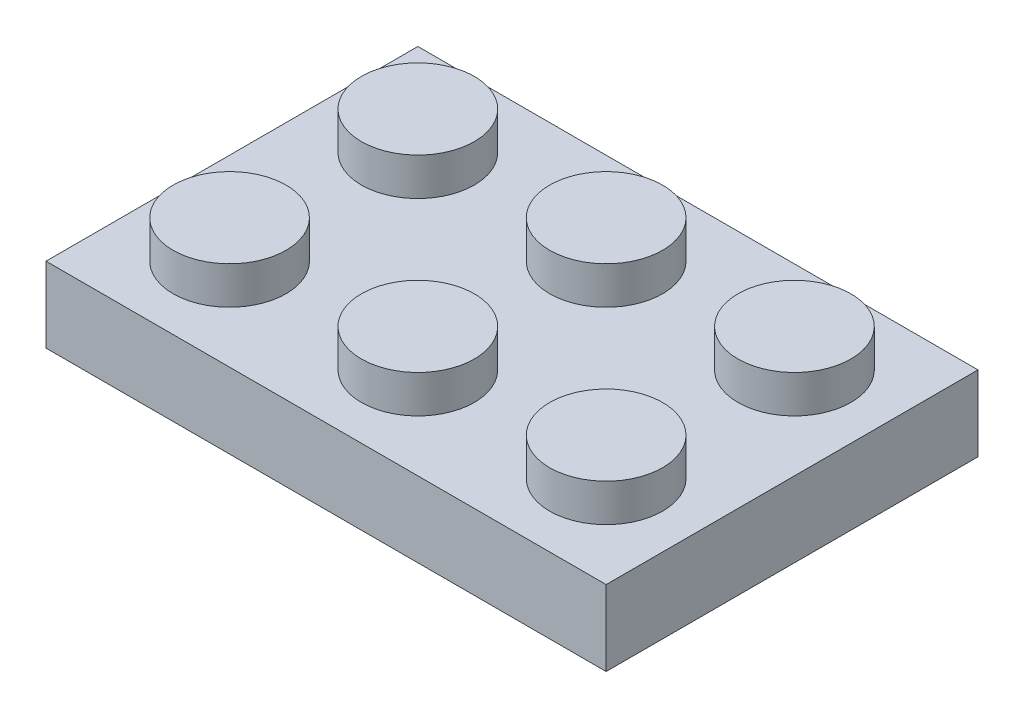
SolidWorks part; units mm, degrees
material "ABS"
ref_plane "Front Plane" through (0, 0, 0) normal (0, 0, 1) x (1, 0, 0)
ref_plane "Top Plane" through (0, 0, 0) normal (0, 1, 0) x (1, 0, 0)
ref_plane "Right Plane" through (0, 0, 0) normal (1, 0, 0) x (0, 0, -1)
sketch "Sketch1" plane through (0, 0, 0) normal (0, 0, 1) x (1, 0, 0)
  line L1 (0, 0) -> (23.8, 0)
  line L2 (0, 0) -> (0, 3.2)
  line L3 (0, 3.2) -> (23.8, 3.2)
  line L4 (23.8, 0) -> (23.8, 3.2)
  dimension "D1" = 3.2
  dimension "D2" = 23.8
extrude "Boss-Extrude1" add sketch "Sketch1" against normal blind 15.8
sketch "Sketch2" plane through (0, 3.2, 0) normal (0, 1, 0) x (1, 0, 0)
  line L0 (0, 15.8) -> (0, 0) construction
  line L1 (23.8, 0) -> (0, 0) construction
  circle A0 centre (3.9, 3.9) radius 2.4
  dimension "D1" = 4.8
  dimension "D2" = 3.9
  dimension "D3" = 3.9
extrude "Boss-Extrude2" add sketch "Sketch2" along normal blind 1.6 contours A0
pattern_linear "LPattern1" count 2 spacing 8 along (0, 0, -1) count 6 spacing 8 along (1, 0, 0) of "Boss-Extrude2"
shell "Shell1" thickness 1.2
sketch "Sketch3" plane through (0, 2, 0) normal (0, -1, 0) x (1, 0, 0)
  line L0 (0, -15.8) -> (0, 0) construction
  line L1 (0, -15.8) -> (23.8, -15.8) construction
  circle A0 centre (7.9, -7.9) radius 3.25
  circle A1 centre (7.9, -7.9) radius 2.4
  dimension "D1" = 4.8
  dimension "D2" = 6.5
  dimension "D3" = 7.9
  dimension "D4" = 7.9
extrude "Boss-Extrude3" add sketch "Sketch3" along normal offset from surface (1.8 mm away) 0.2 up to face at (11.9, 0, -7.9)
pattern_linear "LPattern2" count 2 spacing 8 along (1, 0, 0) of "Boss-Extrude3"
